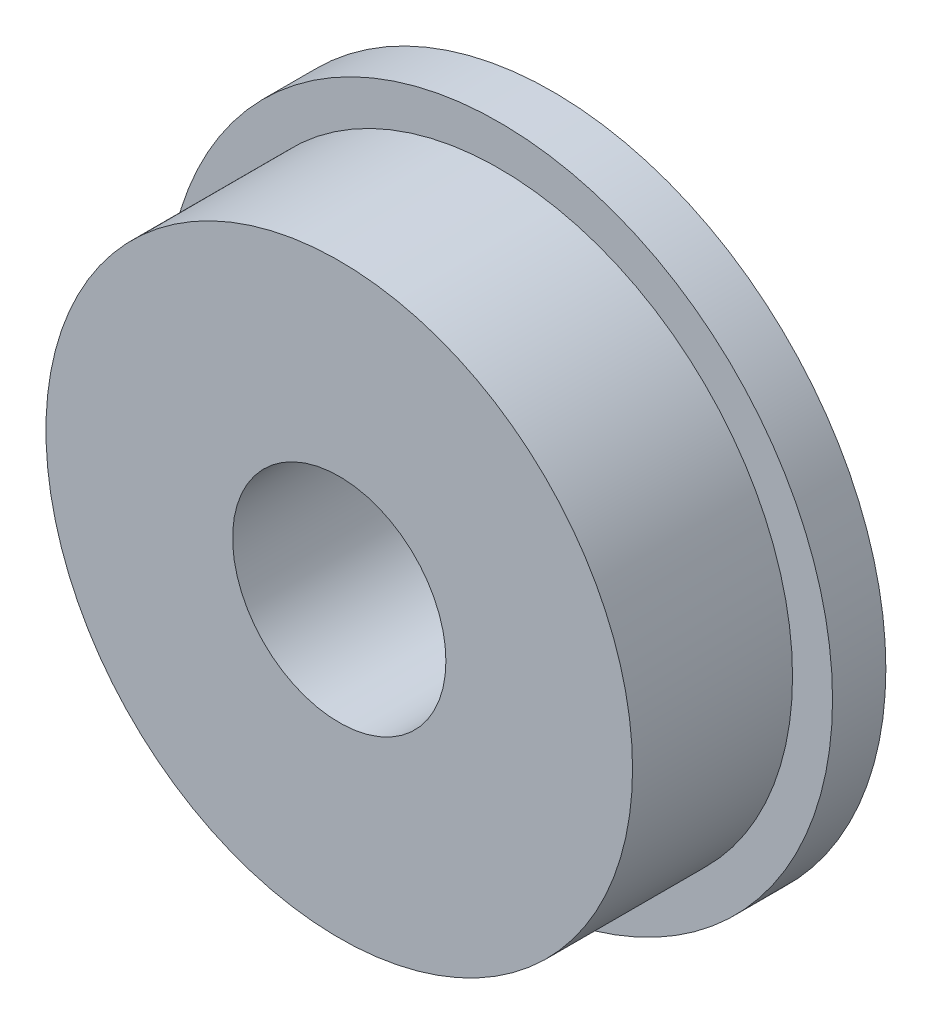
SolidWorks part; units mm, degrees
ref_plane "前视基准面" through (0, 0, 0) normal (0, 0, 1) x (1, 0, 0)
ref_plane "上视基准面" through (0, 0, 0) normal (0, 1, 0) x (1, 0, 0)
ref_plane "右视基准面" through (0, 0, 0) normal (1, 0, 0) x (0, 0, -1)
sketch "草图1" plane through (0, 0, 0) normal (0, 0, 1) x (1, 0, 0)
  circle A0 centre (0, 0) radius 2
  circle A1 centre (0, 0) radius 6.25
  dimension "D1" = 4
  dimension "D2" = 12.5
extrude "凸台-拉伸1" add sketch "草图1" along normal blind 4
sketch "草图2" plane through (0, 0, 4) normal (0, 0, 1) x (1, 0, 0)
  circle A0 centre (0, 0) radius 5.5
  circle A1 centre (0, 0) radius 6.25
  dimension "D1" = 12.5
extrude "切除-拉伸1" cut sketch "草图2" against normal blind 3
